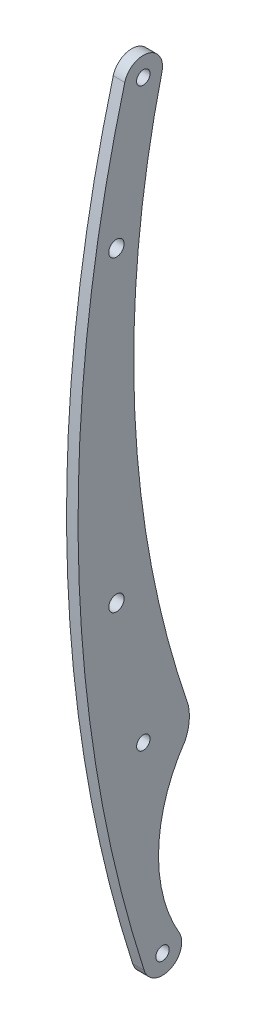
SolidWorks part; units mm, degrees
ref_plane "Alzado" through (0, 0, 0) normal (0, 0, 1) x (1, 0, 0)
ref_plane "Planta" through (0, 0, 0) normal (0, 1, 0) x (1, 0, 0)
ref_plane "Vista lateral" through (0, 0, 0) normal (1, 0, 0) x (0, 0, -1)
sketch "Croquis1" plane through (0, 0, 0) normal (1, 0, 0) x (0, 0, -1)
  line L0 (0, 0) -> (0, -50) construction
  line L1 (0, 0) -> (0, 150) construction
  line L2 (0, -50) -> (5, -50) construction
  line L3 (5, -50) -> (0, 0) construction
  line L4 (-7, 115) -> (-7, -93.0772) construction
  circle A0 centre (5, -50) radius 1.75
  arc A1 (0.2251, -51.4834) -> (9.4477, -47.7156) centre (5, -50) ccw
  arc A2 (4.8586, 148.8192) -> (-4.8311, 151.2885) centre (0, 150) ccw
  arc A3 (4.8586, 148.8192) -> (11.6927, 2.6982) centre (257.5037, 87.4152) ccw
  arc A4 (-4.8311, 151.2885) -> (0.2251, -51.4834) centre (343.009, 58.5131) ccw
  circle A5 centre (0, 150) radius 1.75
  circle A6 centre (0, 0) radius 1.75
  circle A8 centre (-7, 35) radius 2
  circle A9 centre (-7, 115) radius 2
  arc A10 (10.9679, -4.8687) -> (9.4477, -47.7156) centre (43.9572, -27.4897) ccw
  arc A12 (10.9679, -4.8687) -> (11.6927, 2.6982) centre (0, 0) ccw
  dimension "D1" = 4
  dimension "D2" = 50
  dimension "D3" = 5
  dimension "D4" = 150
  dimension "D5" = 5
  dimension "D11" = 260
  dimension "D6" = 80
  dimension "D7" = 7
  dimension "D8" = 35
  dimension "D9" = 12
  dimension "D10" = 5
  dimension "D12" = 360
  dimension "D13" = 40
extrude "Saliente-Extruir1" add sketch "Croquis1" along normal blind 3
